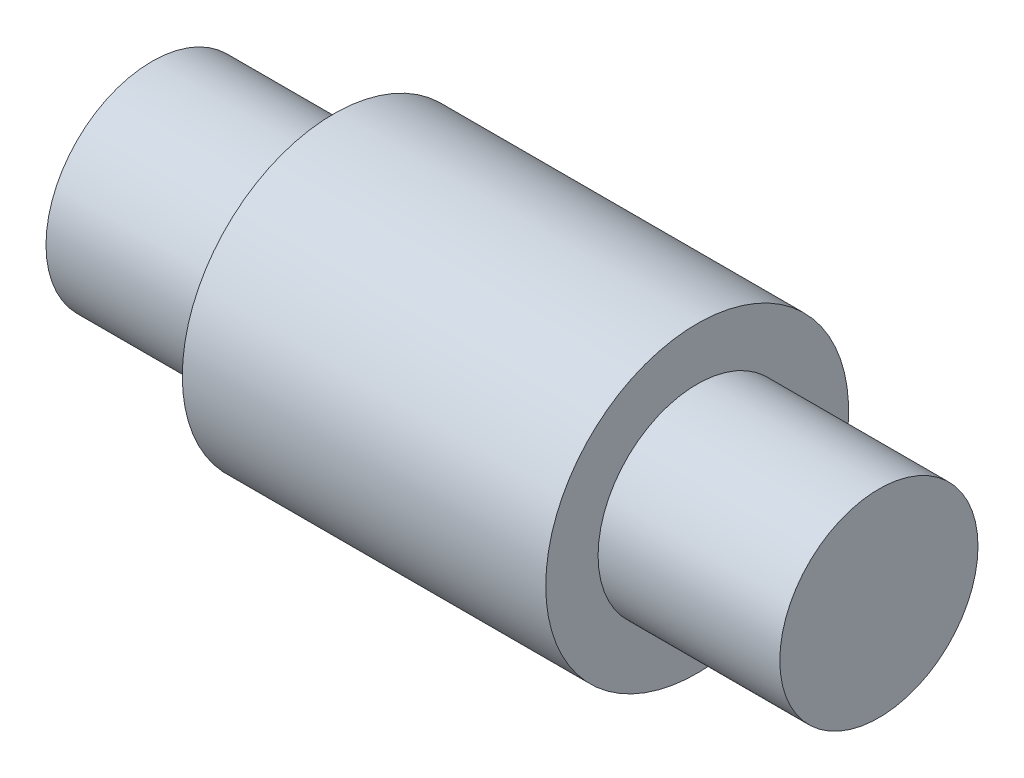
SolidWorks part; units mm, degrees
ref_plane "Front Plane" through (0, 0, 0) normal (0, 0, 1) x (1, 0, 0)
ref_plane "Top Plane" through (0, 0, 0) normal (0, 1, 0) x (1, 0, 0)
ref_plane "Right Plane" through (0, 0, 0) normal (1, 0, 0) x (0, 0, -1)
sketch "Sketch1" plane through (0, 0, 0) normal (0, 0, 1) x (1, 0, 0)
  line L0 (-12, 0) -> (12, 0)
  line L1 (-12, 0) -> (-12, 3.5)
  line L2 (-12, 3.5) -> (-6, 3.5)
  line L3 (-6, 3.5) -> (-6, 5)
  line L4 (-6, 5) -> (6, 5)
  line L5 (6, 5) -> (6, 3.2721)
  line L6 (6, 3.2721) -> (12, 3.2721)
  line L7 (12, 3.2721) -> (12, 0)
  point P4 (0, 0)
  dimension "D1" = 24
  dimension "D2" = 5
  dimension "D3" = 12
revolve "Revolve1" add sketch "Sketch1" angle 360 about L0
